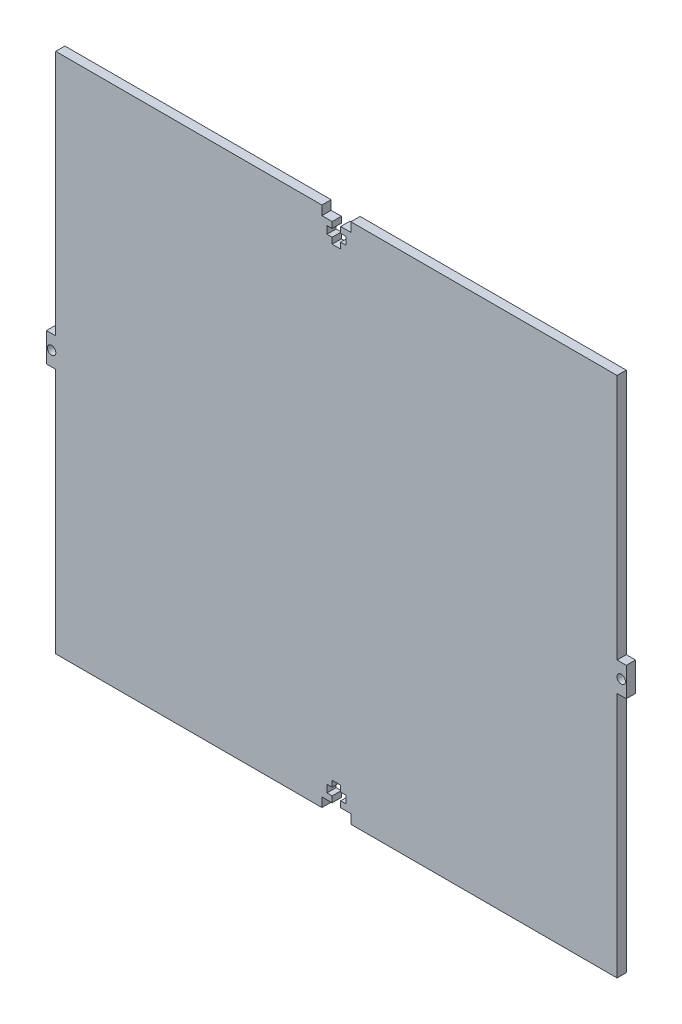
SolidWorks part; units mm, degrees
ref_plane "Front Plane" through (0, 0, 0) normal (0, 0, 1) x (1, 0, 0)
ref_plane "Top Plane" through (0, 0, 0) normal (0, 1, 0) x (1, 0, 0)
ref_plane "Right Plane" through (0, 0, 0) normal (1, 0, 0) x (0, 0, -1)
sketch "Sketch2" plane through (0, 0, 0) normal (0, 0, 1) x (1, 0, 0)
  line L1 (-96.82, -90) -> (96.82, -90)
  line L2 (-96.82, -90) -> (-96.82, 90)
  line L3 (-96.82, 90) -> (96.82, 90)
  line L4 (96.82, -90) -> (96.82, 90)
  line L5 (-96.82, -90) -> (96.82, 90) construction
  line L6 (-96.82, 90) -> (96.82, -90) construction
  point P0 (0, 0)
  dimension "D1" = 180
  dimension "D2" = 193.64
extrude "Boss-Extrude1" add sketch "Sketch2" along normal blind 3.18
sketch "Sketch3" plane through (0, 0, 3.18) normal (0, 0, 1) x (1, 0, 0)
  line L0 (96.82, 90) -> (-96.82, 90) construction
  line L1 (-5, 90) -> (5, 90)
  line L2 (-5, 90) -> (-5, 86.82)
  line L3 (-5, 86.82) -> (-1.47, 86.82)
  line L4 (5, 90) -> (5, 86.82)
  line L5 (0, 90) -> (0, 25.4128) construction
  line L6 (1.47, 82.14) -> (3.25, 82.14)
  line L8 (-1.47, 86.82) -> (-1.47, 84.74)
  line L9 (-1.47, 80.07) -> (1.47, 80.07)
  line L10 (1.47, 86.82) -> (1.47, 84.74)
  line L11 (-3.25, 84.74) -> (-1.47, 84.74)
  line L12 (-3.25, 84.74) -> (-3.25, 82.14)
  line L13 (-3.25, 82.14) -> (-1.47, 82.14)
  line L14 (3.25, 84.74) -> (3.25, 82.14)
  line L15 (-1.47, 82.14) -> (-1.47, 80.07)
  line L16 (1.47, 84.74) -> (3.25, 84.74)
  line L17 (1.47, 86.82) -> (5, 86.82)
  line L18 (1.47, 82.14) -> (1.47, 80.07)
  line L19 (-96.82, 0) -> (96.82, 0) construction
  line L20 (-96.82, 90) -> (-96.82, -90) construction
  line L21 (96.82, -90) -> (96.82, 90) construction
  line L22 (1.47, -86.82) -> (5, -86.82)
  line L23 (5, -90) -> (5, -86.82)
  line L24 (-5, -90) -> (5, -90)
  line L25 (-5, -90) -> (-5, -86.82)
  line L26 (-5, -86.82) -> (-1.47, -86.82)
  line L27 (-1.47, -86.82) -> (-1.47, -84.74)
  line L28 (-3.25, -84.74) -> (-1.47, -84.74)
  line L29 (-3.25, -84.74) -> (-3.25, -82.14)
  line L30 (-3.25, -82.14) -> (-1.47, -82.14)
  line L31 (-1.47, -82.14) -> (-1.47, -80.07)
  line L32 (-1.47, -80.07) -> (1.47, -80.07)
  line L33 (1.47, -82.14) -> (1.47, -80.07)
  line L34 (1.47, -82.14) -> (3.25, -82.14)
  line L35 (3.25, -84.74) -> (3.25, -82.14)
  line L36 (1.47, -84.74) -> (3.25, -84.74)
  line L37 (1.47, -86.82) -> (1.47, -84.74)
  dimension "D1" = 3.18
  dimension "D2" = 10
  dimension "D3" = 2.94
  dimension "D4" = 2.6
  dimension "D5" = 6.75
  dimension "D6" = 6.5
  dimension "D7" = 2.08
extrude "Cut-Extrude1" cut sketch "Sketch3" against normal through all
sketch "Sketch4" plane through (-96.82, 0, 0) normal (-1, 0, 0) x (0, 0, 1)
  line L0 (0, 90) -> (0, -90) construction
  line L1 (0, -5) -> (3.18, -5)
  line L2 (0, -5) -> (0, 5)
  line L3 (0, 5) -> (3.18, 5)
  line L4 (3.18, -5) -> (3.18, 5)
  line L5 (3.18, 90) -> (3.18, -90) construction
  line L6 (0, 0) -> (19.9881, 0) construction
  dimension "D1" = 10
extrude "Boss-Extrude2" add sketch "Sketch4" along normal blind 3.18
sketch "Sketch6" plane through (0, 0, 3.18) normal (0, 0, 1) x (1, 0, 0)
  line L0 (-100, 0) -> (0, 0) construction
  line L1 (-100, -5) -> (-100, 5) construction
  circle A1 centre (-98.25, 0) radius 1.47
  dimension "D1" = 2.94
  dimension "D2" = 1.75
extrude "Cut-Extrude2" cut sketch "Sketch6" against normal through all
mirror "Mirror1" about plane through (0, 0, 0) normal (1, 0, 0) of "Boss-Extrude2"
mirror "Mirror2" about plane through (0, 0, 0) normal (1, 0, 0) of "Cut-Extrude2"
